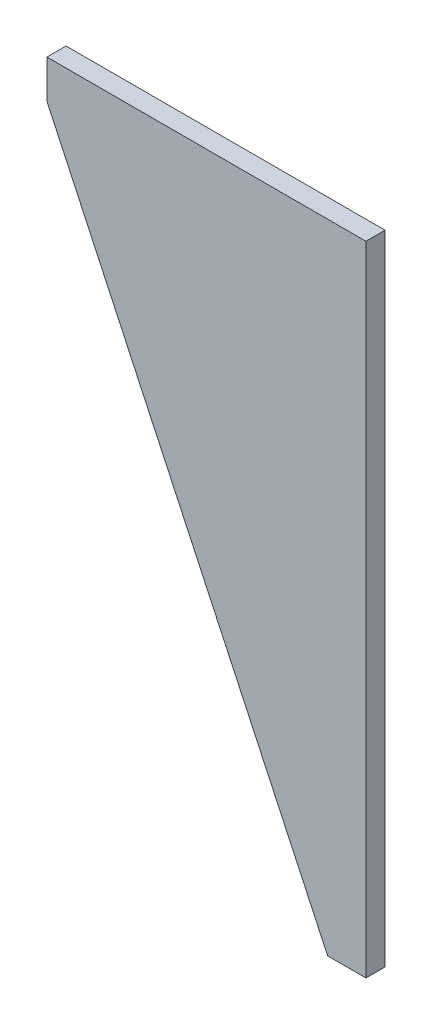
SolidWorks part; units mm, degrees
ref_plane "Спереди" through (0, 0, 0) normal (0, 0, 1) x (1, 0, 0)
ref_plane "Сверху" through (0, 0, 0) normal (0, 1, 0) x (1, 0, 0)
ref_plane "Справа" through (0, 0, 0) normal (1, 0, 0) x (0, 0, -1)
sketch "Эскиз1" plane through (0, 0, 0) normal (0, 0, 1) x (1, 0, 0)
  line L0 (0, -94) -> (-6, -94)
  line L3 (-6, -94) -> (-50, 0)
  line L5 (-50, 0) -> (-50, 6)
  line L7 (-50, 6) -> (0, 6)
  line L8 (0, 6) -> (0, -94)
  line L9 (-6, 0) -> (-6, -123) construction
  line L10 (0, 0) -> (0, -123) construction
  line L11 (0, 6) -> (0, 0) construction
  line L12 (-50, 6) -> (0, 6) construction
  line L13 (-50, 0) -> (0, 0) construction
  dimension "D1" = 50
  dimension "D2" = 100
extrude "Бобышка-Вытянуть1" add sketch "Эскиз1" along normal blind 3 contours L0 L3 L5 L7 L8
